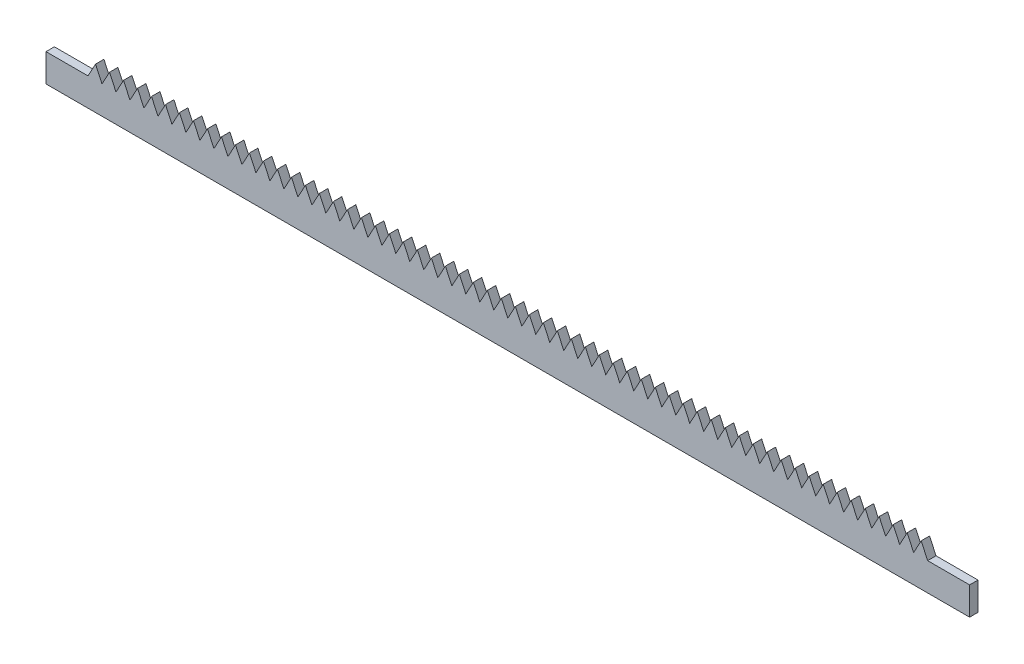
SolidWorks part; units mm, degrees
ref_plane "Alzado" through (0, 0, 0) normal (0, 0, 1) x (1, 0, 0)
ref_plane "Planta" through (0, 0, 0) normal (0, 1, 0) x (1, 0, 0)
ref_plane "Vista lateral" through (0, 0, 0) normal (1, 0, 0) x (0, 0, -1)
sketch "Croquis1" plane through (0, 0, 0) normal (0, 0, 1) x (1, 0, 0)
  line L0 (-150, 2.5) -> (-165, 2.5)
  line L1 (150, -7.5) -> (-150, -7.5)
  line L3 (-165, 2.5) -> (-165, -7.5)
  line L5 (150, -7.5) -> (-150, 7.5) construction
  line L6 (150, 7.5) -> (-150, -7.5) construction
  line L7 (-150, 2.5) -> (-147.2921, 7.5)
  line L8 (-147.2921, 7.5) -> (-145, 2.5)
  line L9 (-145, 2.5) -> (-142.2921, 7.5)
  line L10 (-142.2921, 7.5) -> (-140, 2.5)
  line L11 (-140, 2.5) -> (-137.2921, 7.5)
  line L12 (-137.2921, 7.5) -> (-135, 2.5)
  line L13 (-135, 2.5) -> (-132.2921, 7.5)
  line L14 (-132.2921, 7.5) -> (-130, 2.5)
  line L15 (-130, 2.5) -> (-127.2921, 7.5)
  line L16 (-127.2921, 7.5) -> (-125, 2.5)
  line L17 (-125, 2.5) -> (-122.2921, 7.5)
  line L18 (-122.2921, 7.5) -> (-120, 2.5)
  line L19 (-120, 2.5) -> (-117.2921, 7.5)
  line L20 (-117.2921, 7.5) -> (-115, 2.5)
  line L21 (-115, 2.5) -> (-112.2921, 7.5)
  line L22 (-112.2921, 7.5) -> (-110, 2.5)
  line L23 (-110, 2.5) -> (-107.2921, 7.5)
  line L24 (-107.2921, 7.5) -> (-105, 2.5)
  line L25 (-105, 2.5) -> (-102.2921, 7.5)
  line L26 (-102.2921, 7.5) -> (-100, 2.5)
  line L27 (-100, 2.5) -> (-97.2921, 7.5)
  line L28 (-97.2921, 7.5) -> (-95, 2.5)
  line L29 (-95, 2.5) -> (-92.2921, 7.5)
  line L30 (-92.2921, 7.5) -> (-90, 2.5)
  line L31 (-90, 2.5) -> (-87.2921, 7.5)
  line L32 (-87.2921, 7.5) -> (-85, 2.5)
  line L33 (-85, 2.5) -> (-82.2921, 7.5)
  line L34 (-82.2921, 7.5) -> (-80, 2.5)
  line L35 (-80, 2.5) -> (-77.2921, 7.5)
  line L36 (-77.2921, 7.5) -> (-75, 2.5)
  line L37 (-75, 2.5) -> (-72.2921, 7.5)
  line L38 (-72.2921, 7.5) -> (-70, 2.5)
  line L39 (-70, 2.5) -> (-67.2921, 7.5)
  line L40 (-67.2921, 7.5) -> (-65, 2.5)
  line L41 (-65, 2.5) -> (-62.2921, 7.5)
  line L42 (-62.2921, 7.5) -> (-60, 2.5)
  line L43 (-60, 2.5) -> (-57.2921, 7.5)
  line L44 (-57.2921, 7.5) -> (-55, 2.5)
  line L45 (-55, 2.5) -> (-52.2921, 7.5)
  line L46 (-52.2921, 7.5) -> (-50, 2.5)
  line L47 (-50, 2.5) -> (-47.2921, 7.5)
  line L48 (-47.2921, 7.5) -> (-45, 2.5)
  line L49 (-45, 2.5) -> (-42.2921, 7.5)
  line L50 (-42.2921, 7.5) -> (-40, 2.5)
  line L51 (-40, 2.5) -> (-37.2921, 7.5)
  line L52 (-37.2921, 7.5) -> (-35, 2.5)
  line L53 (-35, 2.5) -> (-32.2921, 7.5)
  line L54 (-32.2921, 7.5) -> (-30, 2.5)
  line L55 (-30, 2.5) -> (-27.2921, 7.5)
  line L56 (-27.2921, 7.5) -> (-25, 2.5)
  line L57 (-25, 2.5) -> (-22.2921, 7.5)
  line L58 (-22.2921, 7.5) -> (-20, 2.5)
  line L59 (-20, 2.5) -> (-17.2921, 7.5)
  line L60 (-17.2921, 7.5) -> (-15, 2.5)
  line L61 (-15, 2.5) -> (-12.2921, 7.5)
  line L62 (-12.2921, 7.5) -> (-10, 2.5)
  line L63 (-10, 2.5) -> (-7.2921, 7.5)
  line L64 (-7.2921, 7.5) -> (-5, 2.5)
  line L65 (-5, 2.5) -> (-2.2921, 7.5)
  line L66 (-2.2921, 7.5) -> (0, 2.5)
  line L67 (0, 2.5) -> (2.7079, 7.5)
  line L68 (2.7079, 7.5) -> (5, 2.5)
  line L69 (5, 2.5) -> (7.7079, 7.5)
  line L70 (7.7079, 7.5) -> (10, 2.5)
  line L71 (10, 2.5) -> (12.7079, 7.5)
  line L72 (12.7079, 7.5) -> (15, 2.5)
  line L73 (15, 2.5) -> (17.7079, 7.5)
  line L74 (17.7079, 7.5) -> (20, 2.5)
  line L75 (20, 2.5) -> (22.7079, 7.5)
  line L76 (22.7079, 7.5) -> (25, 2.5)
  line L77 (25, 2.5) -> (27.7079, 7.5)
  line L78 (27.7079, 7.5) -> (30, 2.5)
  line L79 (30, 2.5) -> (32.7079, 7.5)
  line L80 (32.7079, 7.5) -> (35, 2.5)
  line L81 (35, 2.5) -> (37.7079, 7.5)
  line L82 (37.7079, 7.5) -> (40, 2.5)
  line L83 (40, 2.5) -> (42.7079, 7.5)
  line L84 (42.7079, 7.5) -> (45, 2.5)
  line L85 (45, 2.5) -> (47.7079, 7.5)
  line L86 (47.7079, 7.5) -> (50, 2.5)
  line L87 (50, 2.5) -> (52.7079, 7.5)
  line L88 (52.7079, 7.5) -> (55, 2.5)
  line L89 (55, 2.5) -> (57.7079, 7.5)
  line L90 (57.7079, 7.5) -> (60, 2.5)
  line L91 (60, 2.5) -> (62.7079, 7.5)
  line L92 (62.7079, 7.5) -> (65, 2.5)
  line L93 (65, 2.5) -> (67.7079, 7.5)
  line L94 (67.7079, 7.5) -> (70, 2.5)
  line L95 (70, 2.5) -> (72.7079, 7.5)
  line L96 (72.7079, 7.5) -> (75, 2.5)
  line L97 (75, 2.5) -> (77.7079, 7.5)
  line L98 (77.7079, 7.5) -> (80, 2.5)
  line L99 (80, 2.5) -> (82.7079, 7.5)
  line L100 (82.7079, 7.5) -> (85, 2.5)
  line L101 (85, 2.5) -> (87.7079, 7.5)
  line L102 (87.7079, 7.5) -> (90, 2.5)
  line L103 (90, 2.5) -> (92.7079, 7.5)
  line L104 (92.7079, 7.5) -> (95, 2.5)
  line L105 (95, 2.5) -> (97.7079, 7.5)
  line L106 (97.7079, 7.5) -> (100, 2.5)
  line L107 (100, 2.5) -> (102.7079, 7.5)
  line L108 (102.7079, 7.5) -> (105, 2.5)
  line L109 (105, 2.5) -> (107.7079, 7.5)
  line L110 (107.7079, 7.5) -> (110, 2.5)
  line L111 (110, 2.5) -> (112.7079, 7.5)
  line L112 (112.7079, 7.5) -> (115, 2.5)
  line L113 (115, 2.5) -> (117.7079, 7.5)
  line L114 (117.7079, 7.5) -> (120, 2.5)
  line L115 (120, 2.5) -> (122.7079, 7.5)
  line L116 (122.7079, 7.5) -> (125, 2.5)
  line L117 (125, 2.5) -> (127.7079, 7.5)
  line L118 (127.7079, 7.5) -> (130, 2.5)
  line L119 (130, 2.5) -> (132.7079, 7.5)
  line L120 (132.7079, 7.5) -> (135, 2.5)
  line L121 (135, 2.5) -> (137.7079, 7.5)
  line L122 (137.7079, 7.5) -> (140, 2.5)
  line L123 (140, 2.5) -> (142.7079, 7.5)
  line L124 (142.7079, 7.5) -> (145, 2.5)
  line L125 (145, 2.5) -> (147.7079, 7.5)
  line L126 (147.7079, 7.5) -> (150, 2.5)
  line L127 (-165, -7.5) -> (-150, -7.5)
  line L128 (150, 2.5) -> (165, 2.5)
  line L129 (165, 2.5) -> (165, -7.5)
  line L130 (165, -7.5) -> (150, -7.5)
  point P0 (0, 0)
  dimension "D2" = 15
  dimension "D3" = 300
  dimension "D4" = 5
  dimension "D5" = 60
extrude "Saliente-Extruir1" add sketch "Croquis1" along normal blind 3
